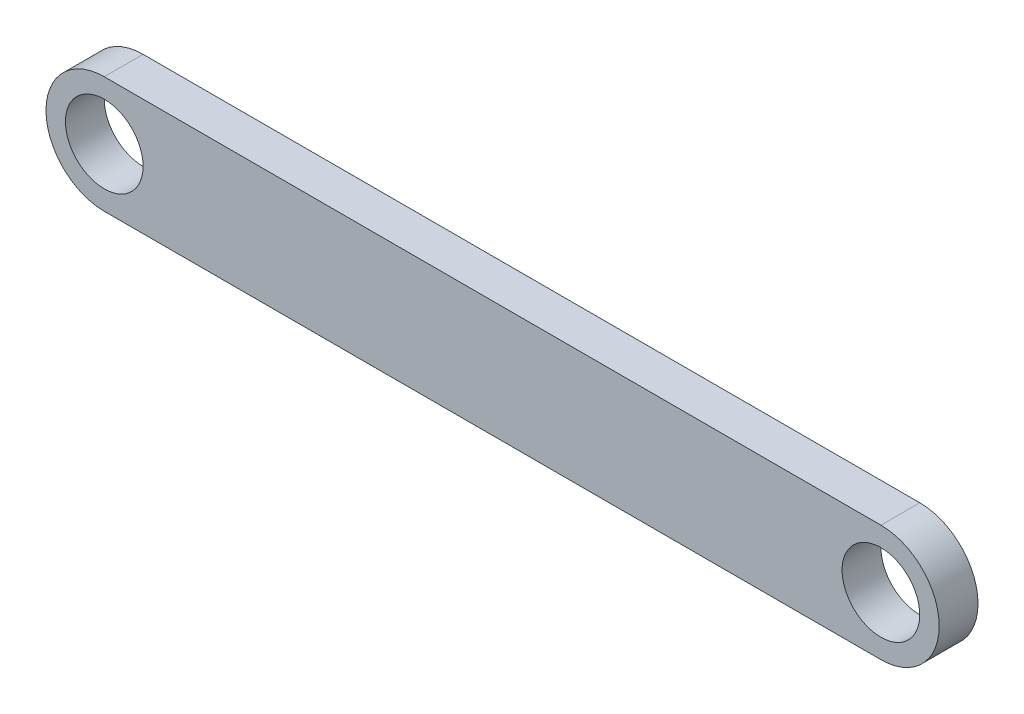
SolidWorks part; units mm, degrees
ref_plane "Front Plane" through (0, 0, 0) normal (0, 0, 1) x (1, 0, 0)
ref_plane "Top Plane" through (0, 0, 0) normal (0, 1, 0) x (1, 0, 0)
ref_plane "Right Plane" through (0, 0, 0) normal (1, 0, 0) x (0, 0, -1)
sketch "Sketch1" plane through (0, 0, 0) normal (0, 0, 1) x (1, 0, 0)
  line L0 (-31.8001, 0) -> (168.1999, 0) construction
  line L1 (-31.8001, 15) -> (168.1999, 15)
  line L2 (-31.8001, -15) -> (168.1999, -15)
  arc A0 (-31.8001, 15) -> (-31.8001, -15) centre (-31.8001, 0) ccw
  arc A1 (168.1999, -15) -> (168.1999, 15) centre (168.1999, 0) ccw
  circle A2 centre (-31.8001, 0) radius 10
  circle A3 centre (168.1999, 0) radius 10
  point P3 (68.1999, 0)
  dimension "D1" = 30
  dimension "D3" = 20
  dimension "D4" = 20
  dimension "D2" = 200
extrude "Boss-Extrude1" add sketch "Sketch1" along normal blind 10
